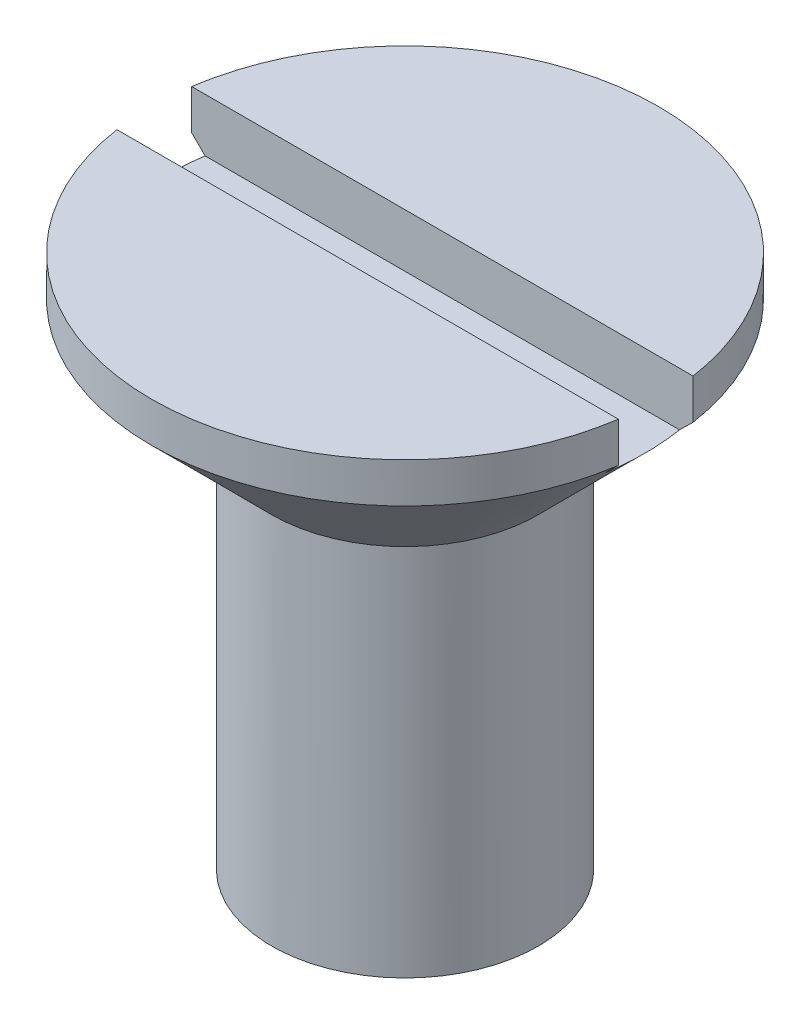
SolidWorks part; units mm, degrees
ref_plane "Спереди" through (0, 0, 0) normal (0, 0, 1) x (1, 0, 0)
ref_plane "Сверху" through (0, 0, 0) normal (0, 1, 0) x (1, 0, 0)
ref_plane "Справа" through (0, 0, 0) normal (1, 0, 0) x (0, 0, -1)
sketch "Эскиз1" plane through (0, 0, 0) normal (0, 0, 1) x (1, 0, 0)
  line L0 (0, 0) -> (0, 4.3334) construction
  line L1 (0, 0) -> (1, 0)
  line L2 (1, 0) -> (1, 2.8)
  line L3 (1, 2.8) -> (1.9, 3.7)
  line L4 (1.9, 3.7) -> (1.9, 4)
  line L5 (1.9, 4) -> (0, 4)
  line L6 (0, 0) -> (0, 4)
  dimension "D1" = 2
  dimension "D2" = 3.8
  dimension "D3" = 45
  dimension "D4" = 1.2
  dimension "D5" = 4
revolve "Основание-Повернуть" add sketch "Эскиз1" angle 360 about L0
sketch "Эскиз2" plane through (0, 4, 0) normal (0, 1, 0) x (-1, 0, 0)
  line L0 (1.1481, 0) -> (-1.0916, 0) construction
  line L1 (-1.8793, -0.28) -> (1.8793, -0.28)
  line L2 (-1.8793, 0.28) -> (1.8793, 0.28)
  circle A0 centre (0, 0) radius 1.9 construction
  arc A1 (-1.8793, 0.28) -> (-1.8793, -0.28) centre (0, 0) ccw
  arc A2 (1.8793, -0.28) -> (1.8793, 0.28) centre (0, 0) ccw
  dimension "D1" = 0.56
extrude "Вырез-Вытянуть1" cut sketch "Эскиз2" against normal blind 0.4
